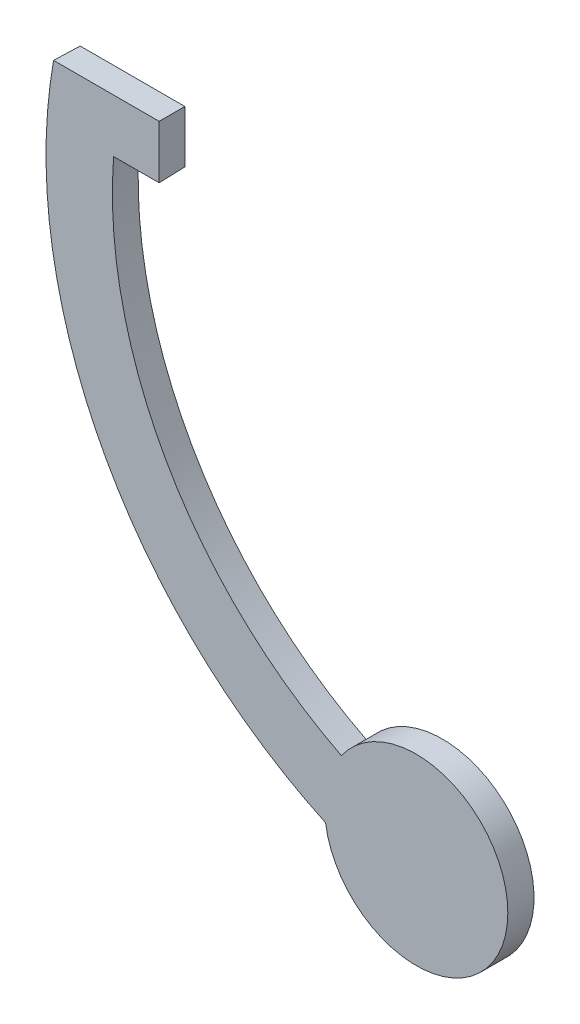
SolidWorks part; units mm, degrees
ref_plane "Front Plane" through (0, 0, 0) normal (0, 0, 1) x (1, 0, 0)
ref_plane "Top Plane" through (0, 0, 0) normal (0, 1, 0) x (1, 0, 0)
ref_plane "Right Plane" through (0, 0, 0) normal (1, 0, 0) x (0, 0, -1)
sketch "Esquisse1" plane through (0, 0, 0) normal (0, 0, 1) x (1, 0, 0)
  line L0 (15.3036, -19.0874) -> (11.0144, -19.0874)
  line L1 (11.0144, -19.0874) -> (10.8051, -15.0929)
  line L2 (10.8051, -15.0929) -> (12.8051, -15.0929)
  line L5 (12.8589, -16.0689) -> (12.8589, -16.0689)
  line L6 (10.8051, -15.0929) -> (11.1133, -15.0929) construction
  line L8 (13.1381, -17.0874) -> (12.9123, -17.0874) construction
  line L9 (12.9123, -17.0874) -> (12.8589, -16.0689) construction
  arc A0 (6.4273, -2.7731) -> (5.3808, -4.4774) centre (0, 0) ccw
  arc A1 (6.4273, -2.7731) -> (5.3808, -4.4774) centre (0, 0) cw
  spline S0 degree 2 poles (6.4273, -2.7731) (14.8442, -7.9413) (15.3036, -19.0874) knots 0 0 0 1 1 1
  spline S1 degree 1 poles (5.3808, -4.4774) (13.1381, -17.0874) knots 0 0 1 1 construction
  spline S2 degree 3 poles (5.3808, -4.4774) (5.9355, -4.818) (7.0272, -5.5707) (8.4292, -6.7961) (9.6558, -8.1519) (10.7017, -9.636) (11.5763, -11.2602) (12.2626, -12.9885) (12.6531, -14.3847) (12.8708, -15.3956) (13.0083, -16.1355) (13.0946, -16.7301) (13.1381, -17.0874) knots 0 0 0 0 0.11207 0.224141 0.336211 0.448282 0.560352 0.672423 0.776105 0.804123 0.840529 0.896564 0.896564 0.896564 0.896564 only from (5.3808, -4.4774) to (12.7965, -15.0534)
  dimension "D1" = 14
  dimension "D2" = 4
  dimension "D3" = 2
  dimension "D5" = 93
  dimension "D4" = 2
extrude "Boss.-Extru.2" add sketch "Esquisse1" along normal blind 2 contours A1 A0
sketch "Esquisse7" plane through (0, 0, 0) normal (0, 0, -1) x (-1, 0, 0)
  line L0 (27.6754, 39.0119) -> (19.6754, 39.0119)
  line L1 (19.6754, 39.0119) -> (19.6754, 35.0119)
  line L2 (19.6754, 35.0119) -> (23.1517, 35.0119)
  arc A0 (6.933, -0.9662) -> (27.6754, 39.0119) centre (-8.7257, 32.5284) ccw
  circle A1 centre (0, 0) radius 7 construction
  arc A2 (23.1517, 35.0119) -> (5.7363, 4.0119) centre (-8.7257, 32.5284) cw
  circle A4 centre (0, 0) radius 7
  arc A5 (6.933, -0.9662) -> (5.7363, 4.0119) centre (0, 0) ccw
  dimension "D5" = 5
  dimension "D1" = 4
  dimension "D2" = 8
  dimension "D3" = 35
  dimension "D4" = 0
extrude "Boss.-Extru.8" add sketch "Esquisse7" against normal blind 2 draft 1 draft outward yes
sketch "Esquisse8" [suppressed] plane through (0, 0, 0) normal (0, 1, 0) x (1, 0, 0)
  line L2 (-31.687, -7) -> (-31.687, -12)
  line L5 (-5.9426, 0) -> (0, 0)
  line L7 (0.0287, -1.9524) -> (-5.9426, -1.9524)
  line L8 (-5.9426, 0) -> (-5.9426, -2) construction
  line L9 (0, 0) -> (0, -18.1521) construction
  line L10 (0, 0) -> (0.0287, -1.9524)
  arc A0 (-5.9426, -1.9524) -> (-31.687, -12) centre (17.4922, -100.004) ccw
  arc A1 (-31.687, -7) -> (-5.9426, 0) centre (-1.5604, -66.9577) cw
  dimension "D1" = 7
  dimension "D2" = 5
